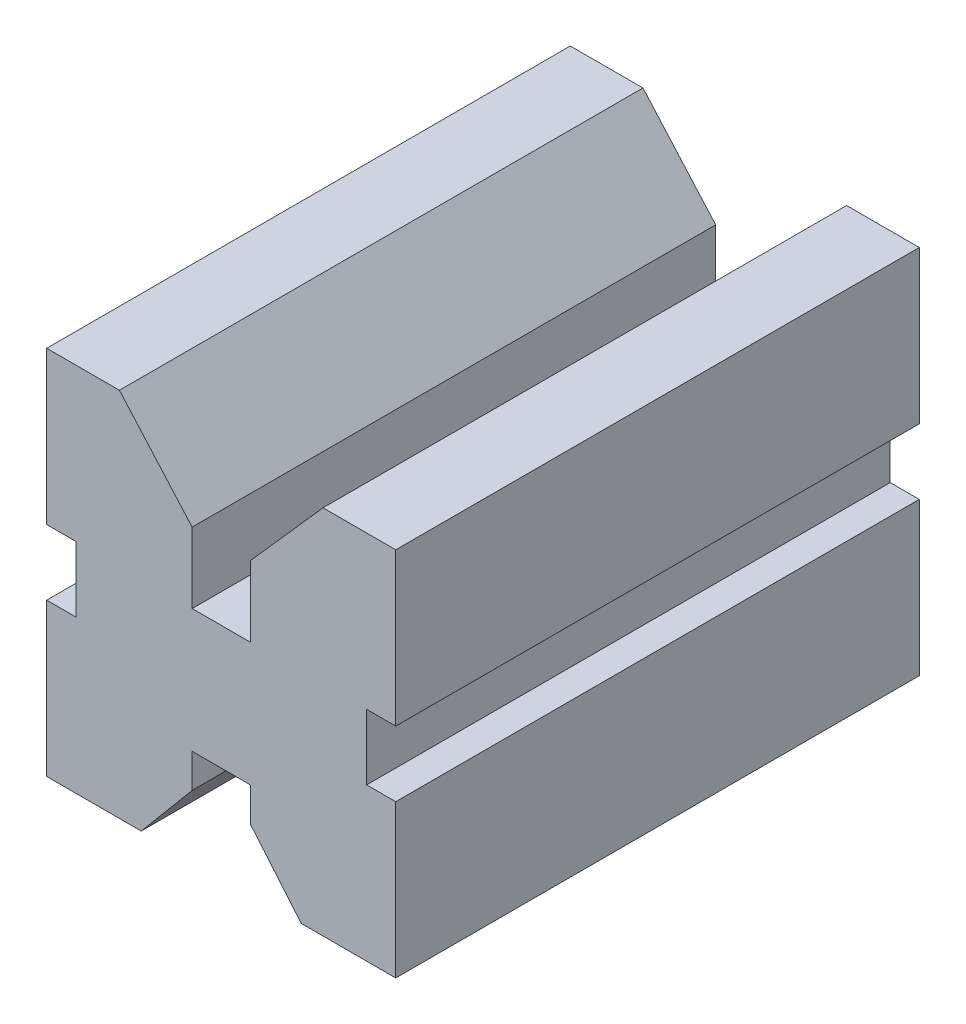
SolidWorks part; units mm, degrees
ref_plane "Front Plane" through (0, 0, 0) normal (0, 0, 1) x (1, 0, 0)
ref_plane "Top Plane" through (0, 0, 0) normal (0, 1, 0) x (1, 0, 0)
ref_plane "Right Plane" through (0, 0, 0) normal (1, 0, 0) x (0, 0, -1)
sketch "Sketch1" plane through (0, 0, 0) normal (0, 0, 1) x (1, 0, 0)
  line L0 (0, 0) -> (39.3231, 0) construction
  line L1 (-24, -25.5) -> (-4, -25.5)
  line L2 (-24, -25.5) -> (-24, -4.5)
  line L3 (-24, 25.5) -> (-4, 25.5)
  line L4 (24, -25.5) -> (24, -4.5)
  line L5 (-24, -25.5) -> (24, 25.5) construction
  line L6 (-24, 25.5) -> (24, -25.5) construction
  line L7 (24, 4.5) -> (20, 4.5)
  line L9 (24, -4.5) -> (20, -4.5)
  line L10 (20, 4.5) -> (20, -4.5)
  line L11 (24, 4.5) -> (24, 25.5)
  line L12 (0, -55) -> (0, 55) construction
  line L13 (-24, -4.5) -> (-20, -4.5)
  line L14 (-20, 4.5) -> (-20, -4.5)
  line L15 (-24, 4.5) -> (-20, 4.5)
  line L16 (-24, 4.5) -> (-24, 25.5)
  line L17 (0, 0) -> (0, -14.4059) construction
  line L19 (-4, 25.5) -> (-4, 4.5)
  line L20 (-4, 4.5) -> (4, 4.5)
  line L21 (4, 25.5) -> (4, 4.5)
  line L22 (4, 25.5) -> (24, 25.5)
  line L23 (4, -25.5) -> (24, -25.5)
  line L25 (-4, -25.5) -> (-4, -12.5)
  line L26 (-4, -12.5) -> (4, -12.5)
  line L27 (4, -25.5) -> (4, -12.5)
  point P0 (0, 0)
  dimension "D1" = 48
  dimension "D2" = 51
  dimension "D3" = 9
  dimension "D4" = 4
  dimension "D5" = 8
  dimension "D6" = 21
  dimension "D7" = 13
extrude "Boss-Extrude1" add sketch "Sketch1" along normal mid plane 72
sketch "Sketch2" plane through (0, 0, 0) normal (0, 0, 1) x (1, 0, 0)
  line L0 (-14, 25.5) -> (-4, 14.1971)
  line L2 (4, 25.5) -> (4, 4.5) construction
  line L3 (4, 14.1971) -> (14, 25.5)
  line L4 (-4, 4.5) -> (-4, 25.5) construction
  line L5 (-14, 25.5) -> (14, 25.5)
  line L6 (0, 0) -> (0, -20.63) construction
  line L7 (-4, 25.5) -> (-24, 25.5) construction
  line L8 (-4, 14.1971) -> (4, 14.1971)
  line L10 (24, 25.5) -> (4, 25.5) construction
  dimension "D1" = 83
extrude "Cut-Extrude1" cut sketch "Sketch2" against normal through all both and the other way through all
sketch "Sketch3" plane through (0, 0, 0) normal (0, 0, 1) x (1, 0, 0)
  line L0 (4, -17.1577) -> (11, -25.5)
  line L1 (4, -12.5) -> (4, -25.5) construction
  line L2 (4, -25.5) -> (24, -25.5) construction
  line L3 (-4, -17.1577) -> (-11, -25.5)
  line L4 (-4, -25.5) -> (-4, -12.5) construction
  line L5 (-24, -25.5) -> (-4, -25.5) construction
  line L6 (0, 0) -> (0, -7.3319) construction
  line L7 (-11, -25.5) -> (11, -25.5)
  line L8 (-4, -17.1577) -> (4, -17.1577)
  line L9 (24, -25.5) -> (24, -4.5) construction
  dimension "D1" = 80
  dimension "D2" = 13
extrude "Cut-Extrude2" cut sketch "Sketch3" against normal through all both and the other way through all
